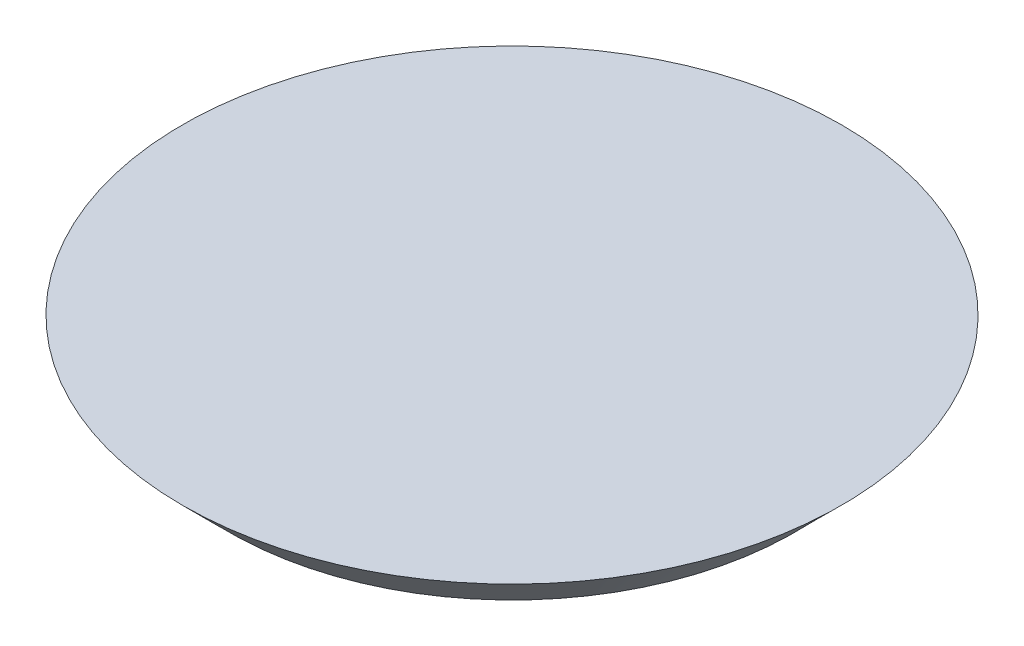
SolidWorks part; units mm, degrees
ref_plane "Front Plane" through (0, 0, 0) normal (0, 0, 1) x (1, 0, 0)
ref_plane "Top Plane" through (0, 0, 0) normal (0, 1, 0) x (1, 0, 0)
ref_plane "Right Plane" through (0, 0, 0) normal (1, 0, 0) x (0, 0, -1)
sketch "Sketch1" plane through (0, 0, 0) normal (0, 0, 1) x (1, 0, 0)
  line L0 (0, -6.4742) -> (0, 8.3803) construction
  line L1 (0, 2.939) -> (7, 2.939)
  line L2 (7, 2.939) -> (6, 1.939)
  line L3 (6, 1.939) -> (0, 1.939)
  line L4 (0, 2.939) -> (0, 1.939)
  dimension "D1" = 7
  dimension "D2" = 6
  dimension "D3" = 1
revolve "Foot Revolve" add sketch "Sketch1" angle 360 about L0
